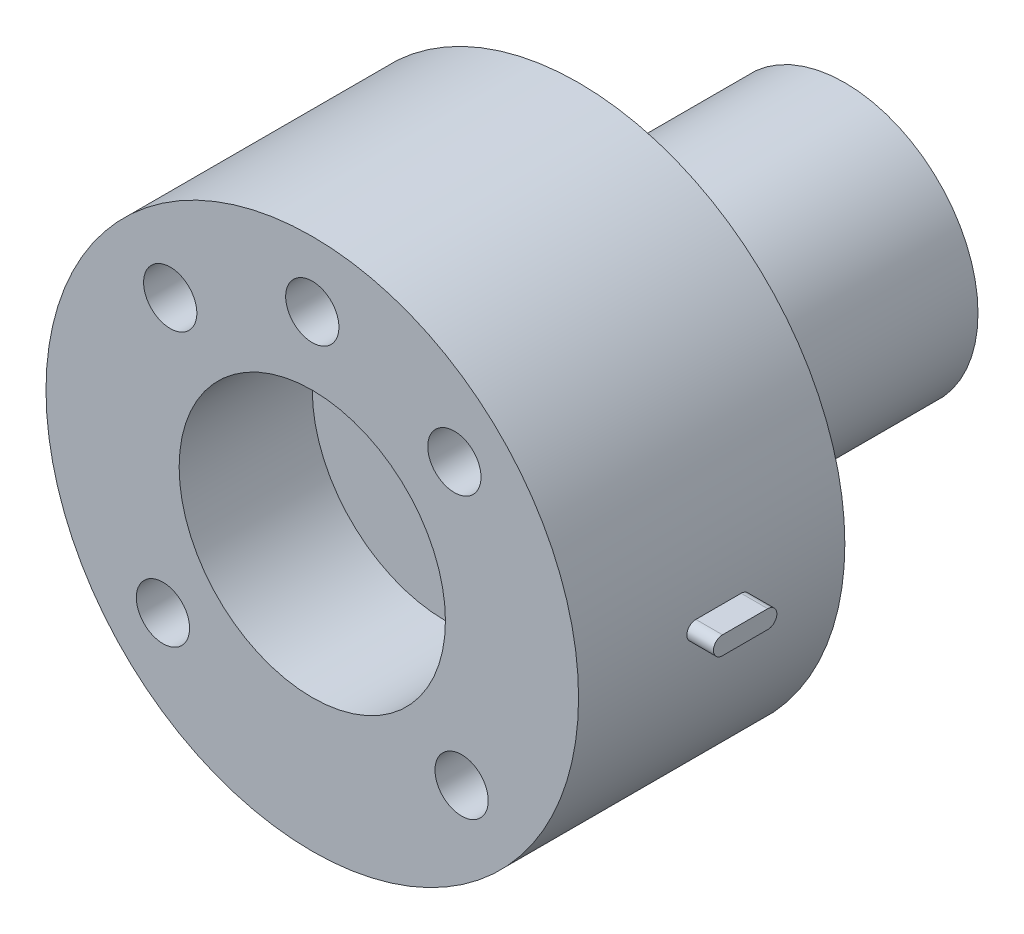
SolidWorks part; units mm, degrees
material "6061-T6 (SS)"
ref_plane "Front Plane" through (0, 0, 0) normal (0, 0, 1) x (1, 0, 0)
ref_plane "Top Plane" through (0, 0, 0) normal (0, 1, 0) x (1, 0, 0)
ref_plane "Right Plane" through (0, 0, 0) normal (1, 0, 0) x (0, 0, -1)
sketch "Sketch1" plane through (0, 0, 0) normal (0, 0, 1) x (1, 0, 0)
  circle A0 centre (0, 0) radius 20
extrude "Boss-Extrude1" add sketch "Sketch1" along normal blind 20
sketch "Sketch2" plane through (0, 0, 0) normal (0, 0, -1) x (-1, 0, 0)
  circle A0 centre (0, 0) radius 10
extrude "Boss-Extrude2" add sketch "Sketch2" along normal blind 20
sketch "Sketch3" plane through (0, 0, 20) normal (0, 0, 1) x (1, 0, 0)
  circle A0 centre (0, 0) radius 10
extrude "Cut-Extrude1" cut sketch "Sketch3" against normal blind 10
sketch "Sketch9" plane through (0, 0, 20) normal (0, 0, 1) x (1, 0, 0)
  line L0 (0, -20) -> (0, 20) construction
  circle A0 centre (0, 0) radius 20 construction
  circle A1 centre (0, 15.0911) radius 2
  circle A2 centre (10.671, 10.671) radius 2
  circle A3 centre (11.2149, -10.0979) radius 2
  circle A4 centre (-11.2149, -10.0979) radius 2
  circle A5 centre (-10.671, 10.671) radius 2
  point P11 (0, 0)
  point P15 (0, 0)
  dimension "D1" = 2
  dimension "D2" = 2
extrude "Cut-Extrude2" cut sketch "Sketch9" against normal blind 5
ref_plane "Plane1" through (20, 0, 0) normal (1, 0, 0) x (0, 0, -1)
sketch "Sketch10" plane through (20, 0, 0) normal (1, 0, 0) x (0, 0, -1)
  line L0 (-11.1885, 0) -> (-7.7895, 0) construction
  line L1 (-11.1885, 0.6798) -> (-7.7895, 0.6798)
  line L2 (-11.1885, -0.6798) -> (-7.7895, -0.6798)
  arc A0 (-11.1885, 0.6798) -> (-11.1885, -0.6798) centre (-11.1885, 0) ccw
  arc A1 (-7.7895, -0.6798) -> (-7.7895, 0.6798) centre (-7.7895, 0) ccw
  point P2 (-9.489, 0)
extrude "Boss-Extrude3" add sketch "Sketch10" along normal blind 2 separate body
ref_plane "Plane2" through (0, 0, 0) normal (1, 0, 0) x (0, 0, -1)
sketch "Sketch11" plane through (0, 0, 0) normal (1, 0, 0) x (0, 0, -1)
  line L0 (0, 0) -> (-20, 0) construction
  line L1 (-20, 20) -> (-20, -20) construction
